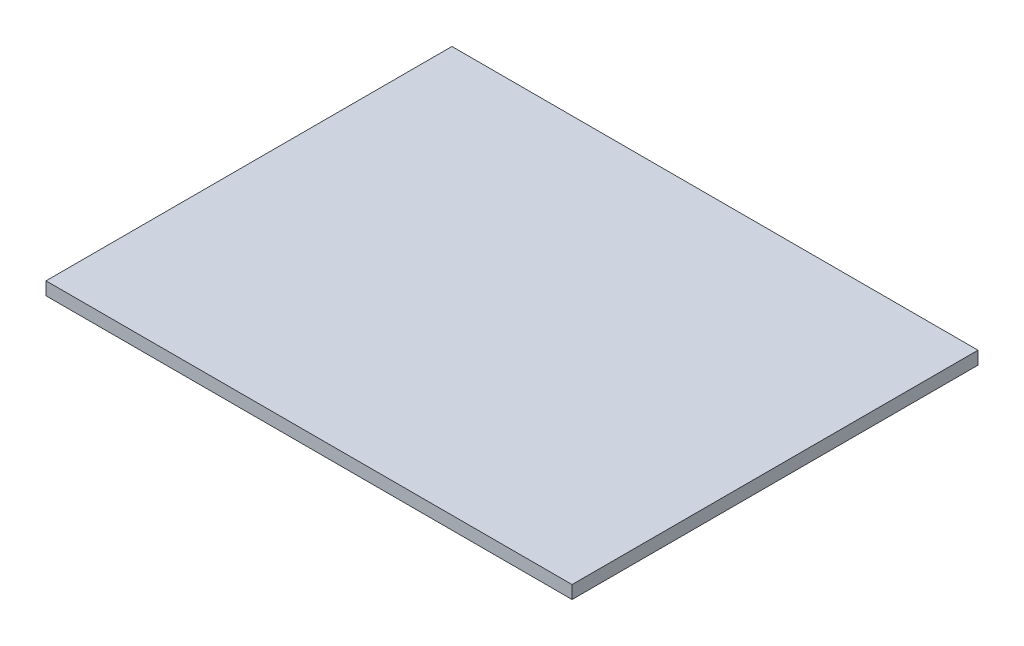
SolidWorks part; units mm, degrees
ref_plane "Спереди" through (0, 0, 0) normal (0, 0, 1) x (1, 0, 0)
ref_plane "Сверху" through (0, 0, 0) normal (0, 1, 0) x (1, 0, 0)
ref_plane "Справа" through (0, 0, 0) normal (1, 0, 0) x (0, 0, -1)
sketch "Эскиз1" plane through (0, 0, 0) normal (0, 1, 0) x (1, 0, 0)
  line L1 (-61.7074, 455.4174) -> (586.2926, 455.4174)
  line L2 (-61.7074, 455.4174) -> (-61.7074, -44.5826)
  line L3 (-61.7074, -44.5826) -> (586.2926, -44.5826)
  line L4 (586.2926, 455.4174) -> (586.2926, -44.5826)
  dimension "D1" = 648
  dimension "D2" = 500
extrude "Бобышка-Вытянуть1" add sketch "Эскиз1" along normal blind 16
